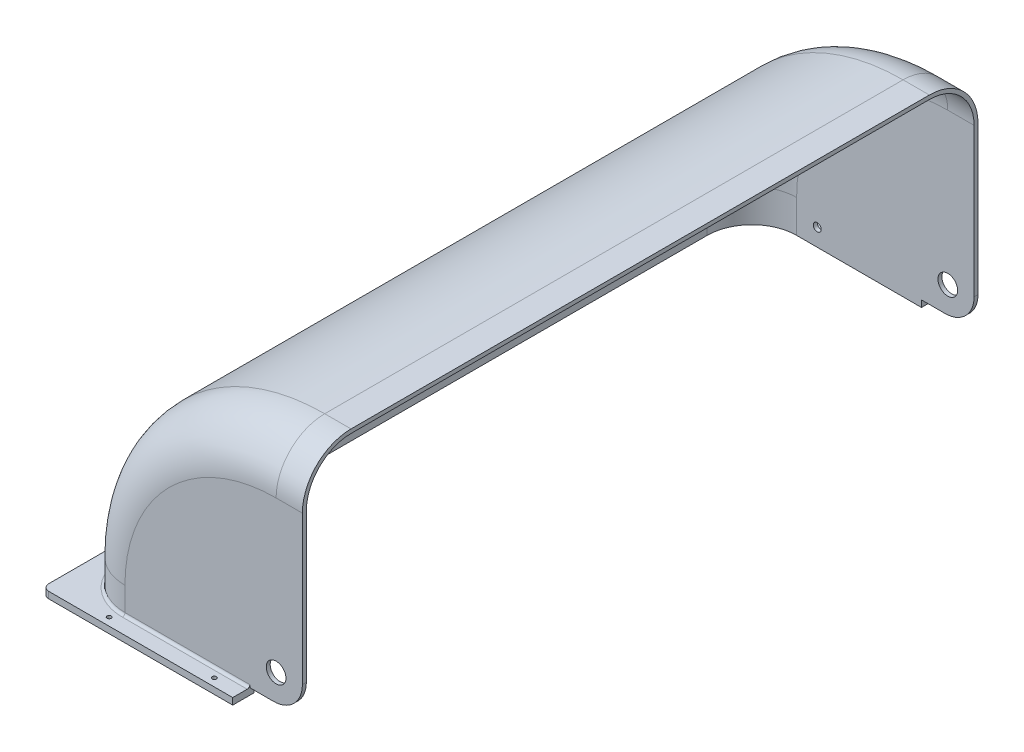
SolidWorks part; units mm, degrees
ref_plane "Front Plane" through (0, 0, 0) normal (0, 0, 1) x (1, 0, 0)
ref_plane "Top Plane" through (0, 0, 0) normal (0, 1, 0) x (1, 0, 0)
ref_plane "Right Plane" through (0, 0, 0) normal (1, 0, 0) x (0, 0, -1)
sketch "Sketch1" plane through (0, 0, 0) normal (0, 1, 0) x (1, 0, 0)
  line L0 (0, -254) -> (0, 254) construction
  line L2 (-165, 270) -> (-165, -270)
  line L5 (-165, 270) -> (0, 0) construction
  line L6 (-165, -270) -> (0, 0) construction
  line L9 (-149, -254) -> (-149, 254)
  line L11 (-149, 254) -> (0, 254)
  line L12 (-165, 270) -> (0, 270)
  line L21 (-149, -254) -> (0, -254)
  line L22 (-165, -270) -> (0, -270)
  line L23 (0, 254) -> (0, 270)
  line L24 (0, -254) -> (0, -270)
  line L25 (0, 270) -> (0, 264) construction
  line L26 (0, 264) -> (-40, 264) construction
  line L27 (-40, 264) -> (-120, 264) construction
  line L28 (-165, 0) -> (-159, 0) construction
  line L29 (-159, 0) -> (-159, 50) construction
  line L30 (-159, 50) -> (-159, 130) construction
  line L31 (0, 0) -> (-149, 0) construction
  line L32 (-159, 210) -> (-159, 50) construction
  line L33 (-40, -264) -> (-120, -264) construction
  line L34 (-159, -210) -> (-159, -50) construction
  line L35 (-159, -50) -> (-159, -130) construction
  circle A0 centre (-159, 130) radius 1.6
  circle A1 centre (-159, 50) radius 1.6
  circle A2 centre (-120, 264) radius 1.6
  circle A3 centre (-40, 264) radius 1.6
  circle A4 centre (-159, 210) radius 1.6
  circle A5 centre (-40, -264) radius 1.6
  circle A6 centre (-120, -264) radius 1.6
  circle A7 centre (-159, -210) radius 1.6
  circle A8 centre (-159, -50) radius 1.6
  circle A9 centre (-159, -130) radius 1.6
  point P0 (0, 0)
  point P9 (0, 0)
  point P26 (-159, 130)
  point P38 (-159, -130)
  dimension "D13" = 80
  dimension "D1" = 16
  dimension "D2" = 540
  dimension "D3" = 16
  dimension "D4" = 16
  dimension "D5" = 165
  dimension "D6" = 165
  dimension "D7" = 6
  dimension "D8" = 80
  dimension "D9" = 40
  dimension "D10" = 6
  dimension "D11" = 50
  dimension "D12" = 80
extrude "Boss-Extrude1" add sketch "Sketch1" along normal blind 5
sketch "Sketch12" plane through (0, 5, 0) normal (0, 1, 0) x (1, 0, 0)
  line L0 (0, -254) -> (-149, -254) construction
  line L1 (0, 254) -> (-149, 254)
  line L2 (0, 254) -> (0, -254) construction
  line L3 (0, -254) -> (-149, -254)
  line L4 (-149, 254) -> (-149, -254)
  line L5 (0, 257) -> (-152, 257)
  line L6 (-152, 257) -> (-152, -257)
  line L7 (0, -257) -> (-152, -257)
  line L8 (0, 257) -> (0, 254)
  line L9 (0, -257) -> (0, -254)
  dimension "D1" = 3
extrude "Boss-Extrude5" add sketch "Sketch12" along normal blind 20
fillet "Fillet8" radius 34 2 edges at (-149, 12.5, 254) (-149, 12.5, -254)
fillet "Fillet9" radius 37 2 edges at (-152, 15, -257) (-152, 15, 257)
sketch "Sketch13" plane through (0, 25, 0) normal (0, 1, 0) x (1, 0, 0)
  line L0 (0, 254) -> (-115, 254)
  line L1 (0, 257) -> (-115, 257)
  line L2 (0, 257) -> (0, -257) construction
  line L3 (0, -257) -> (-115, -257)
  line L4 (-152, 220) -> (-152, -220)
  line L5 (-149, 220) -> (-149, -220)
  line L6 (0, -254) -> (-115, -254)
  line L7 (0, 257) -> (0, 254)
  line L8 (0, -257) -> (0, -254)
  arc A0 (-115, 257) -> (-152, 220) centre (-115, 220) ccw
  arc A1 (-115, -257) -> (-152, -220) centre (-115, -220) cw
  arc A2 (-115, 254) -> (-149, 220) centre (-115, 220) ccw
  arc A3 (-115, -254) -> (-149, -220) centre (-115, -220) cw
  dimension "D3" = 37
  dimension "D4" = 37
  dimension "D1" = 152
  dimension "D2" = 514
  dimension "D5" = 3
revolve "Revolve4" add sketch "Sketch13" angle 90 about L2
sketch "Sketch15" plane through (0, 0, 0) normal (1, 0, 0) x (0, 0, -1)
  line L0 (-254, 5) -> (-254, 140)
  line L1 (-257, 5) -> (257, 5) construction
  line L2 (-257, 5) -> (-257, 140)
  line L3 (-220, 177) -> (220, 177)
  line L4 (257, 5) -> (257, 140)
  line L5 (-220, 174) -> (220, 174)
  line L6 (254, 5) -> (254, 140)
  line L7 (-257, 5) -> (-270, 5)
  line L8 (-270, 5) -> (-270, 0)
  line L9 (-270, 0) -> (-254, 0)
  line L10 (-254, 0) -> (-254, 5)
  line L11 (254, 5) -> (254, 0)
  line L12 (254, 0) -> (270, 0)
  line L13 (270, 0) -> (270, 5)
  line L14 (270, 5) -> (257, 5)
  arc A0 (-220, 177) -> (-257, 140) centre (-220, 140) ccw
  arc A1 (257, 140) -> (220, 177) centre (220, 140) ccw
  arc A2 (-220, 174) -> (-254, 140) centre (-220, 140) ccw
  arc A3 (254, 140) -> (220, 174) centre (220, 140) ccw
  dimension "D3" = 37
  dimension "D4" = 37
  dimension "D1" = 514
  dimension "D2" = 172
  dimension "D5" = 3
extrude "Boss-Extrude6" add sketch "Sketch15" along normal blind 20
sketch "Sketch16" plane through (0, 0, 270) normal (0, 0, 1) x (1, 0, 0)
  line L0 (-115, 5) -> (20, 5) construction
  line L1 (20, 0) -> (-20, 0)
  line L2 (20, 0) -> (20, 5)
  line L3 (20, 5) -> (-20, 5)
  line L4 (-20, 0) -> (-20, 5)
  dimension "D1" = 40
  dimension "D2" = 5
extrude "Cut-Extrude3" cut sketch "Sketch16" against normal up to surface (540 mm away) up to face at (-72.5, 2.5, -270)
fillet "Fillet10" radius 22 2 edges at (20, 5, 255.5) (20, 5, -255.5)
sketch "Sketch17" plane through (0, 0, 257) normal (0, 0, 1) x (1, 0, 0)
  line L0 (-115, 25) -> (20, 25) construction
  line L1 (20, 140) -> (20, 27) construction
  line L2 (0, 140) -> (0, 0) construction
  arc A0 (0, 140) -> (-115, 25) centre (0, 25) ccw construction
  circle A1 centre (0, 25) radius 7.5
  dimension "D1" = 25
extrude "Cut-Extrude4" cut sketch "Sketch17" against normal up to surface (514 mm away) up to face at (-33.0373, 52.323, -257)
fillet "Fillet11" radius 5 2 edges at (-165, 2.5, -270) (-165, 2.5, 270)
fillet "Fillet12" radius 2 5 edges at (-67.5, 5, -257) (-141.163, 5, -246.163) (-67.5, 5, 257) (-141.163, 5, 246.163) (-152, 5, 0)
sketch "Sketch18" plane through (0, 0, -257) normal (0, 0, -1) x (-1, 0, 0)
  line L0 (0, 25) -> (152, 7) construction
  line L1 (152, 25) -> (152, 7) construction
  line L2 (115, 7) -> (152, 7) construction
  line L3 (0, 25) -> (99.3061, 13.2401) construction
  circle A0 centre (99.3061, 13.2401) radius 3
  dimension "D2" = 6
  dimension "D1" = 100
extrude "Cut-Extrude5" cut sketch "Sketch18" against normal up to surface (7 mm away)
